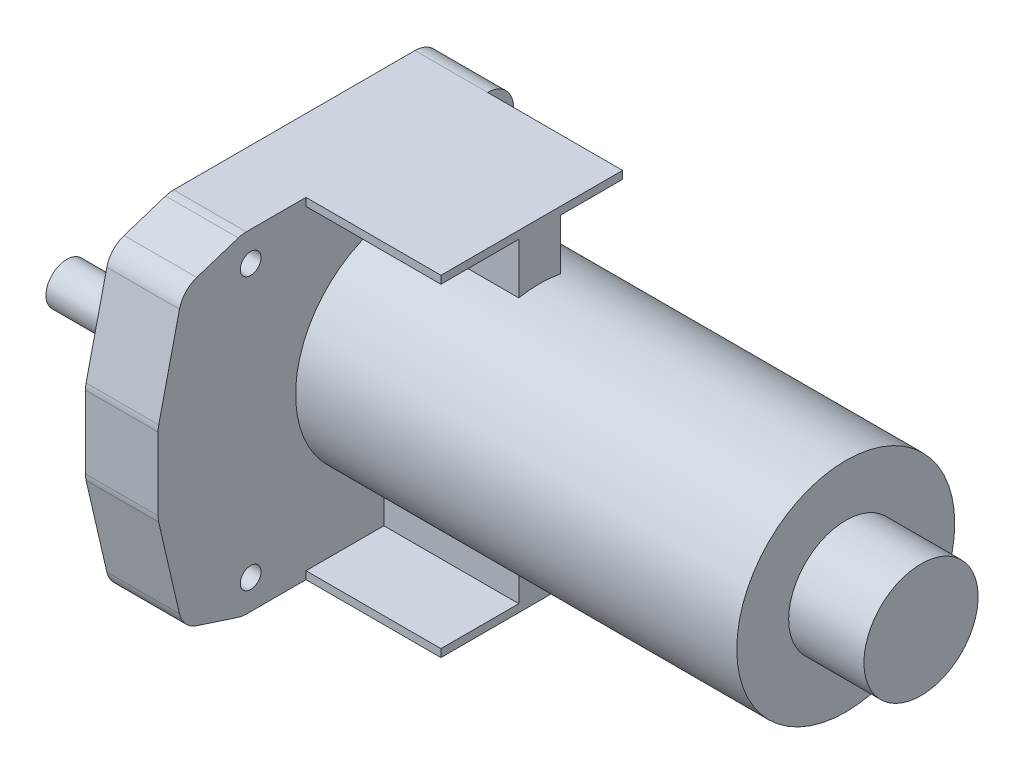
SolidWorks part; units mm, degrees
material "AISI 1020"
ref_plane "Plan de face" through (0, 0, 0) normal (0, 0, 1) x (1, 0, 0)
ref_plane "Plan de dessus" through (0, 0, 0) normal (0, 1, 0) x (1, 0, 0)
ref_plane "Plan de droite" through (0, 0, 0) normal (1, 0, 0) x (0, 0, -1)
sketch "Esquisse1" plane through (0, 0, 0) normal (1, 0, 0) x (0, 0, -1)
  line L0 (67.8364, 0) -> (-61.451, 0) construction
  line L3 (-6, 31.9) -> (40.5, 31.9)
  line L4 (-15.5448, 29.0565) -> (-7.5448, 31.6554)
  line L5 (-22.8716, 8.1188) -> (-18.8716, 25.427)
  line L18 (-23, 6.993) -> (-23, -6.993)
  line L19 (-22.8716, -8.1188) -> (-18.8716, -25.427)
  line L20 (-15.5448, -29.0565) -> (-7.5448, -31.6554)
  line L21 (-6, -31.9) -> (40.5, -31.9)
  line L22 (45.5, -26.9) -> (45.5, 26.9)
  arc A0 (40.5, 31.9) -> (45.5, 26.9) centre (40.5, 26.9) cw
  arc A1 (-7.5448, 31.6554) -> (-6, 31.9) centre (-6, 26.9) cw
  arc A2 (-18.8716, 25.427) -> (-15.5448, 29.0565) centre (-14, 24.3011) cw
  arc A3 (-23, 6.993) -> (-22.8716, 8.1188) centre (-18, 6.993) cw
  circle A4 centre (38.44, -26.2) radius 2
  circle A5 centre (-5.16, -26.2) radius 2
  circle A6 centre (-5.16, 26.2) radius 2
  circle A7 centre (38.44, 26.2) radius 2
  arc A19 (-23, -6.993) -> (-22.8716, -8.1188) centre (-18, -6.993) ccw
  arc A20 (-18.8716, -25.427) -> (-15.5448, -29.0565) centre (-14, -24.3011) ccw
  arc A21 (-7.5448, -31.6554) -> (-6, -31.9) centre (-6, -26.9) ccw
  arc A22 (40.5, -31.9) -> (45.5, -26.9) centre (40.5, -26.9) ccw
  dimension "D5" = 5
  dimension "D6" = 43.6
  dimension "D9" = 9
  dimension "D7" = 4
  dimension "D1" = 63.8
  dimension "D2" = 68.5
  dimension "D3" = 23
  dimension "D4" = 13.9859
  dimension "D8" = 24.3011
  dimension "D10" = 17
  dimension "D11" = 52.4
  dimension "D12" = 5.16
extrude "Extrusion3" add sketch "Esquisse1" along normal blind 14
sketch "Esquisse3" plane through (14, 0, 0) normal (1, 0, 0) x (0, 0, -1)
  circle A0 centre (24.5, 0) radius 21
  dimension "D1" = 42
  dimension "D2" = 24.5
extrude "Extrusion4" add sketch "Esquisse3" along normal blind 85
sketch "Esquisse4" plane through (0, 0, 0) normal (1, 0, 0) x (0, 0, -1)
  circle A0 centre (0, 0) radius 4
  dimension "D1" = 8
extrude "Extrusion5" add sketch "Esquisse4" against normal blind 26.6
sketch "Esquisse5" plane through (0, 0, 0) normal (1, 0, 0) x (0, 0, -1)
  circle A0 centre (0, 0) radius 7.25
  dimension "D1" = 14.5
extrude "Extrusion6" add sketch "Esquisse5" against normal blind 5
sketch "Esquisse6" plane through (99, 0, 0) normal (1, 0, 0) x (0, 0, -1)
  line L0 (24.5, 14) -> (24.5, 21)
  line L1 (24.5, -14) -> (24.5, -21)
  arc A0 (24.5, 21) -> (24.5, -21) centre (24.5, 0) cw
  circle A1 centre (24.5, 0) radius 21 construction
  arc A2 (24.5, -14) -> (24.5, 14) centre (24.5, 0) cw
  dimension "D1" = 14
extrude "Extrusion7" [suppressed] add sketch "Esquisse6" along normal blind 18
sketch "Esquisse7" [suppressed] plane through (117, 0, 0) normal (1, 0, 0) x (0, 0, -1)
  line L0 (43.9165, 8) -> (34.5, 8)
  line L1 (34.5, 8) -> (34.5, -8)
  line L2 (34.5, -8) -> (43.9165, -8)
  arc A0 (43.9165, 8) -> (43.9165, -8) centre (24.5, 0) cw
  arc A1 (24.5, -21) -> (24.5, 21) centre (24.5, 0) ccw construction
  dimension "D1" = 16
  dimension "D2" = 11
extrude "Extrusion8" [suppressed] add sketch "Esquisse7" along normal blind 5
sketch "Esquisse8" plane through (14, 0, 0) normal (1, 0, 0) x (0, 0, -1)
  line L0 (40.5, 31.9) -> (5.5, 31.9)
  line L1 (40.5, 31.9) -> (-6, 31.9) construction
  line L2 (5.5, 31.9) -> (5.5, 30.4)
  line L3 (5.5, 30.4) -> (20.5, 30.4)
  line L4 (20.5, 30.4) -> (20.5, 13.1472)
  line L5 (20.5, 13.1472) -> (28.5, 13.1472)
  line L6 (28.5, 13.1472) -> (28.5, 30.4)
  line L7 (28.5, 30.4) -> (40.5, 30.4)
  line L8 (40.5, 30.4) -> (40.5, 31.9)
  line L9 (24.5, 11.1603) -> (24.5, -22.6325) construction
  line L10 (40.5, 0) -> (-9.3952, 0) construction
  line L11 (40.5, -30.4) -> (40.5, -31.9)
  line L12 (28.5, -30.4) -> (40.5, -30.4)
  line L13 (28.5, -13.1472) -> (28.5, -30.4)
  line L14 (20.5, -13.1472) -> (28.5, -13.1472)
  line L15 (20.5, -30.4) -> (20.5, -13.1472)
  line L16 (5.5, -30.4) -> (20.5, -30.4)
  line L17 (5.5, -31.9) -> (5.5, -30.4)
  line L18 (40.5, -31.9) -> (5.5, -31.9)
  circle A0 centre (24.5, 0) radius 21 construction
  point P7 (24.5, 0)
  dimension "D1" = 1.5
  dimension "D2" = 35
  dimension "D3" = 8
extrude "Extrusion9" add sketch "Esquisse8" along normal blind 26
sketch "Esquisse9" plane through (99, 0, 0) normal (1, 0, 0) x (0, 0, -1)
  circle A0 centre (24.5, 0) radius 11
  dimension "D1" = 22
extrude "Extrusion10" add sketch "Esquisse9" along normal blind 14.5
